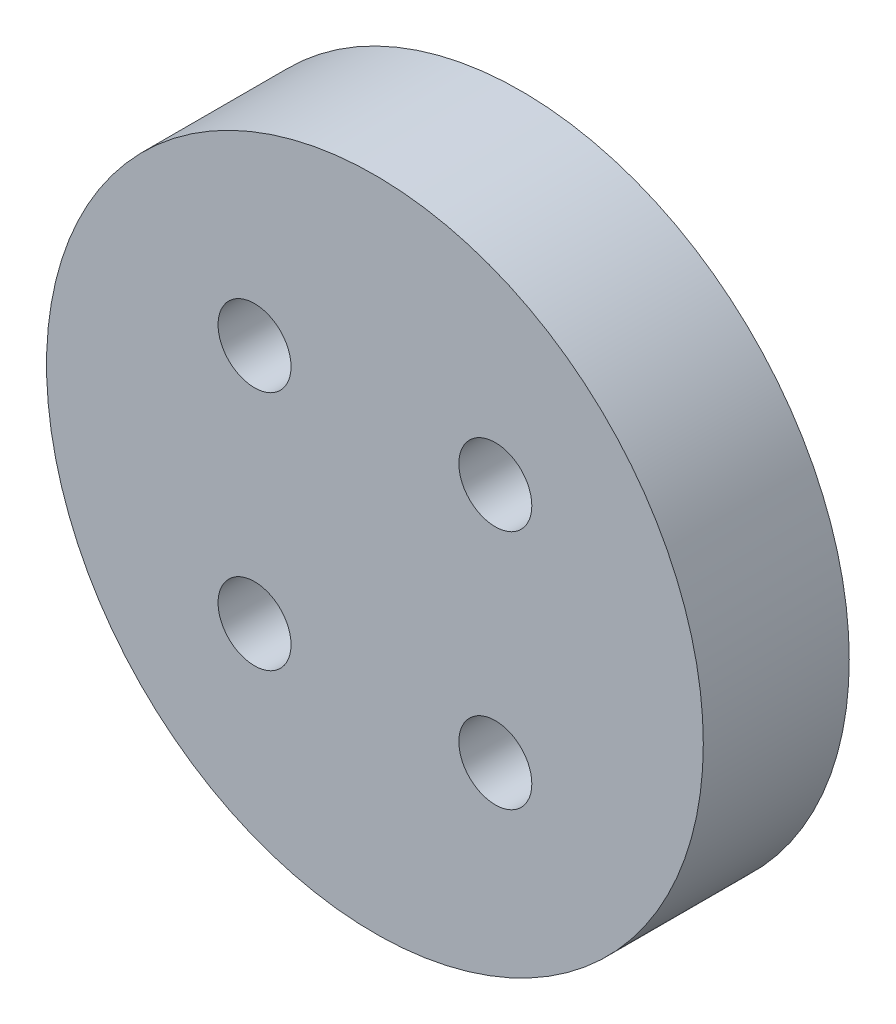
SolidWorks part; units mm, degrees
ref_plane "Alzado" through (0, 0, 0) normal (0, 0, 1) x (1, 0, 0)
ref_plane "Planta" through (0, 0, 0) normal (0, 1, 0) x (1, 0, 0)
ref_plane "Vista lateral" through (0, 0, 0) normal (1, 0, 0) x (0, 0, -1)
sketch "Croquis1" plane through (0, 0, 0) normal (0, 0, 1) x (1, 0, 0)
  circle A0 centre (0, 0) radius 13.5
  dimension "D1" = 27
extrude "Saliente-Extruir1" add sketch "Croquis1" along normal blind 6
sketch "Croquis3" plane through (0, 0, 0) normal (0, 0, -1) x (-1, 0, 0)
  line L0 (0, 0) -> (50000, 0) construction
  line L1 (13.5, 0) -> (13.5, 8.4265) construction
  circle A0 centre (10.5, 0) radius 1.575
  circle A1 centre (-7.5, 0) radius 1.575
  circle A2 centre (0, 0) radius 13.5 construction
  dimension "D1" = 3.15
  dimension "D2" = 18
  dimension "D3" = 3
extrude "Cortar-Extruir1" cut sketch "Croquis3" against normal blind 1.8
sketch "Croquis10" plane through (0, 0, 6) normal (0, 0, 1) x (1, 0, 0)
  line L0 (4.9497, -4.9497) -> (-4.9497, 4.9497) construction
  line L1 (-4.9497, -4.9497) -> (4.9497, 4.9497) construction
  line L2 (200000, 0) -> (-250000, 0) construction
  circle A0 centre (0, 0) radius 7 construction
  dimension "D1" = 14
  dimension "D2" = 45
hole_wizard "Diámetro de taladro Ø3.0 (3)2" positions "Croquis12" profile "Croquis13" hole size "Ø3.0" standard "ISO"
sketch "Croquis12" plane through (0, 0, 6) normal (0, 0, 1) x (1, 0, 0)
  point P0 (-4.9497, 4.9497)
  point P3 (-4.9497, -4.9497)
  point P6 (4.9497, -4.9497)
  point P9 (4.9497, 4.9497)
sketch "Croquis13" plane through (-4.9497, 4.9497, 6) normal (1, 0, 0) x (0, -1, 0)
  line L0 (0, 0) -> (0, 50.9013)
  line L1 (0, 50.9013) -> (1.5, 50)
  line L2 (1.5, 50) -> (1.5, 0)
  line L5 (1.5, 0) -> (0, 0)
  line L10 (0, 50.9013) -> (-1.5, 50) construction
  line L11 (0, -6.35) -> (0, 107.95) construction
  dimension "Diámetro de taladro" = 3
  dimension "Profundidad de taladro" = 50
  dimension "Ángulo de perforador" = 118
